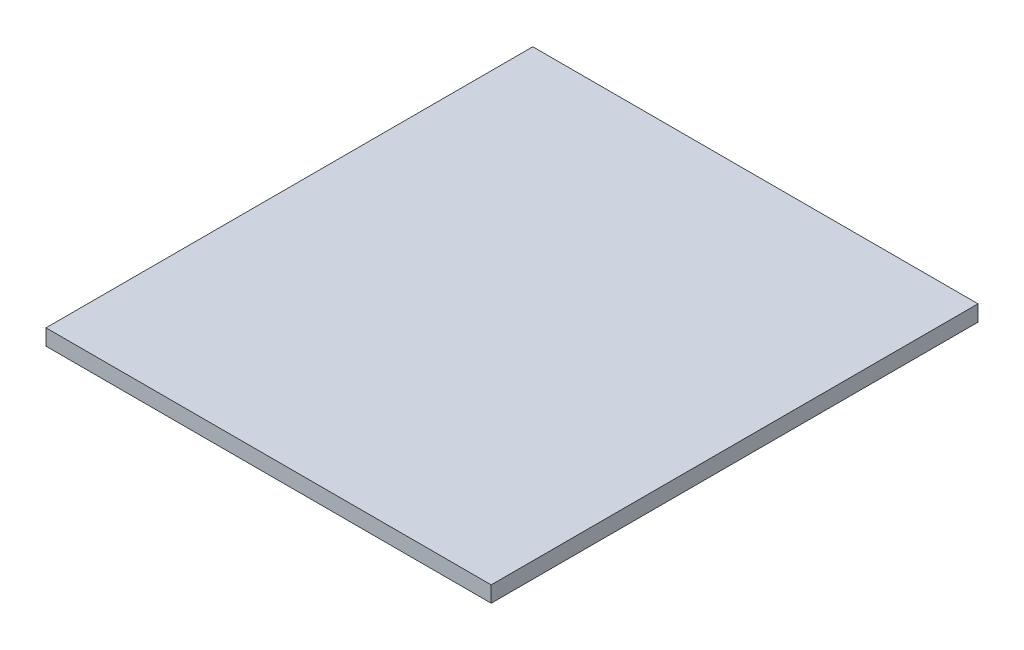
SolidWorks part; units mm, degrees
ref_plane "Front Plane" through (0, 0, 0) normal (0, 0, 1) x (1, 0, 0)
ref_plane "Top Plane" through (0, 0, 0) normal (0, 1, 0) x (1, 0, 0)
ref_plane "Right Plane" through (0, 0, 0) normal (1, 0, 0) x (0, 0, -1)
sketch "Sketch1" plane through (0, 0, 0) normal (0, 1, 0) x (1, 0, 0)
  line L1 (-251.5, 275) -> (251.5, 275)
  line L2 (-251.5, 275) -> (-251.5, -275)
  line L3 (-251.5, -275) -> (251.5, -275)
  line L4 (251.5, 275) -> (251.5, -275)
  line L5 (-251.5, 275) -> (251.5, -275) construction
  line L6 (-251.5, -275) -> (251.5, 275) construction
  point P0 (0, 0)
  dimension "D1" = 550
  dimension "D2" = 503
extrude "Boss-Extrude1" add sketch "Sketch1" along normal blind 18
